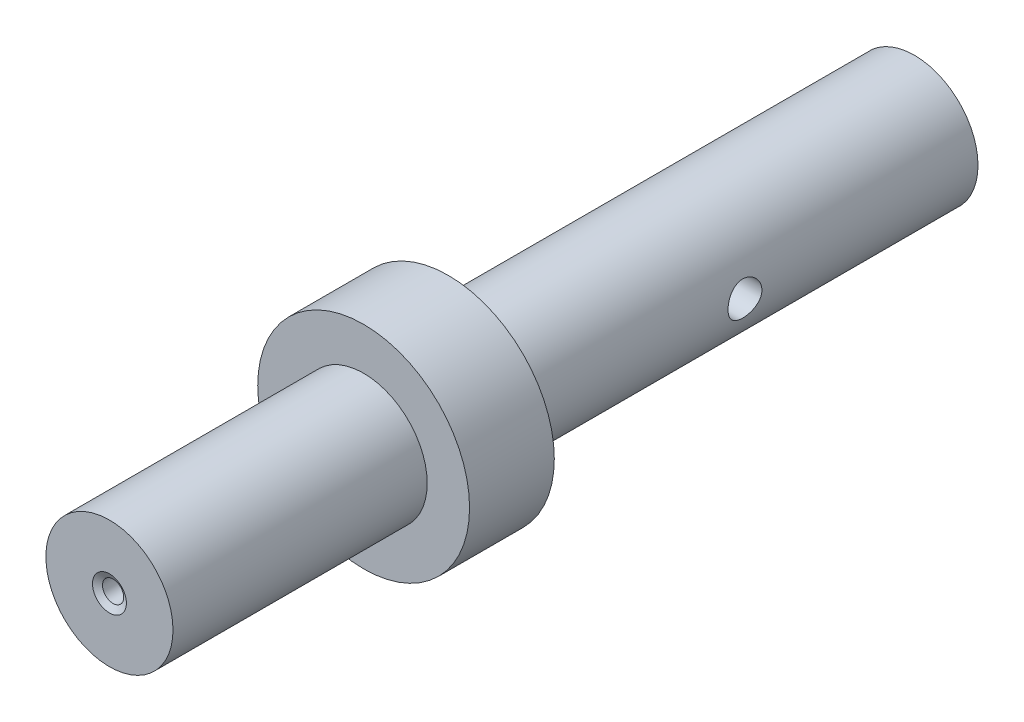
SolidWorks part; units mm, degrees
material "Chrome Stainless Steel"
ref_plane "Front Plane" through (0, 0, 0) normal (0, 0, 1) x (1, 0, 0)
ref_plane "Top Plane" through (0, 0, 0) normal (0, 1, 0) x (1, 0, 0)
ref_plane "Right Plane" through (0, 0, 0) normal (1, 0, 0) x (0, 0, -1)
sketch "Sketch1" plane through (0, 0, 0) normal (0, 0, 1) x (1, 0, 0)
  circle A0 centre (0, 0) radius 12.5
  dimension "D1" = 25
extrude "25mm dia" add sketch "Sketch1" along normal blind 10
sketch "Sketch2" plane through (0, 0, 10) normal (0, 0, 1) x (1, 0, 0)
  circle A0 centre (0, 0) radius 7.5
  dimension "D1" = 15
extrude "15mm dia bearing end" add sketch "Sketch2" along normal blind 40 from surface at -10 starting at face at (12.5, 0, 0)
sketch "Sketch3" plane through (0, 0, 0) normal (0, 0, -1) x (-1, 0, 0)
  circle A0 centre (0, 0) radius 7.5
  dimension "D1" = 15
extrude "15mm dia gear end" add sketch "Sketch3" along normal blind 55
hole_wizard "M3x0.5 Tapped Hole1" positions "Sketch6" profile "Sketch5" tap size "M3x0.5" standard "ANSI Metric"
sketch "Sketch6" plane through (0, 0, 40) normal (0, 0, 1) x (1, 0, 0)
  point P0 (0, 0)
sketch "Sketch5" plane through (0, 0, 40) normal (1, 0, 0) x (0, -1, 0)
  line L0 (0, 0) -> (0, 15.7511)
  line L1 (0, 15.7511) -> (1.25, 15)
  line L2 (1.25, 15) -> (1.25, 0.433)
  line L3 (1.25, 0.433) -> (2, 0)
  line L5 (2, 0) -> (0, 0)
  line L6 (-1.25, 0.433) -> (-2, 0) construction
  line L10 (0, 15.7511) -> (-1.25, 15) construction
  line L11 (0, -6.35) -> (0, 107.95) construction
  dimension "Tap Drill Dia." = 2.5
  dimension "Tap Drill Depth" = 15
  dimension "Near C'Sink Dia." = 4
  dimension "Near C'Sink Angle" = 120
  dimension "Drill Angle" = 118
cosmetic thread "Hole Thread1" parameters "D1"=12, "D2"=3
ref_plane "Plane1" through (7.5, 0, 0) normal (1, 0, 0) x (0, 0, -1)
sketch "Sketch7" plane through (7.5, 0, 0) normal (1, 0, 0) x (0, 0, -1)
  line L0 (0, 0) -> (55, 0) construction
  line L1 (55, -7.5) -> (55, 7.5) construction
  line L2 (0, 0) -> (27.5, 0)
  circle A0 centre (27.5, 0) radius 2
  dimension "D2" = 4
  dimension "D1" = 27.5
extrude "Cut-Extrude1" cut sketch "Sketch7" against normal through all contours A0
equation "\"a\"= 1"
equation "\"b\"= 1"
equation "\"c\"= 1"
equation "\"d\"= 1"
equation "\"e\"= 1"
equation "\"x\"= 1"
equation "\"y\"= 1"
equation "\"z\"= 1"
